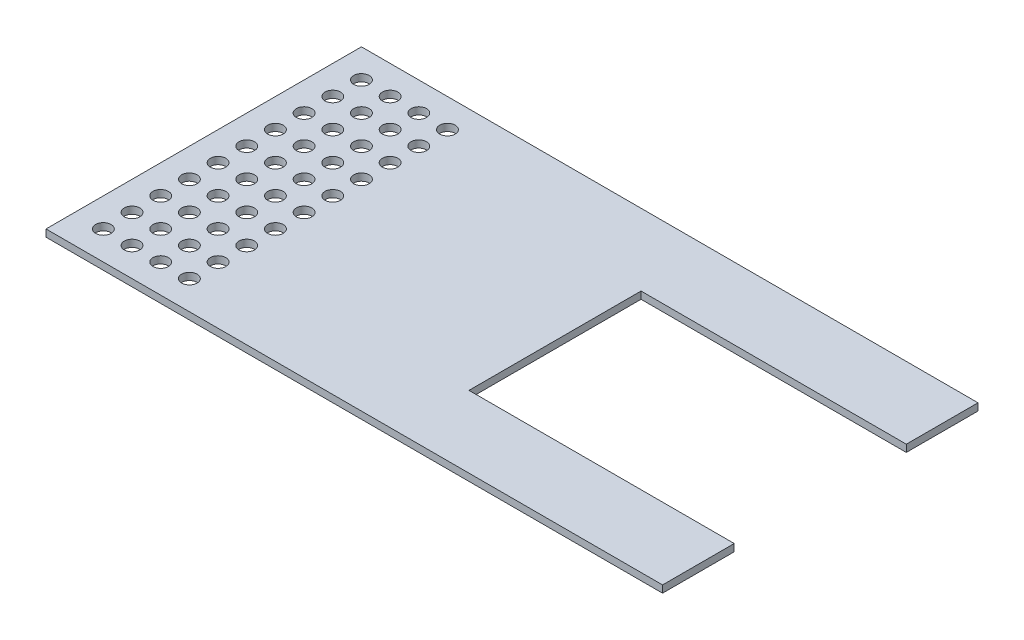
SolidWorks part; units mm, degrees
ref_plane "Front Plane" through (0, 0, 0) normal (0, 0, 1) x (1, 0, 0)
ref_plane "Top Plane" through (0, 0, 0) normal (0, 1, 0) x (1, 0, 0)
ref_plane "Right Plane" through (0, 0, 0) normal (1, 0, 0) x (0, 0, -1)
sketch "Sketch1" plane through (0, 0, 0) normal (0, 1, 0) x (1, 0, 0)
  line L1 (-101.6, -66.675) -> (101.6, -66.675)
  line L2 (-101.6, -66.675) -> (-101.6, 66.675)
  line L3 (-101.6, 66.675) -> (101.6, 66.675)
  line L4 (101.6, -66.675) -> (101.6, 66.675)
  line L5 (-101.6, -66.675) -> (101.6, 66.675) construction
  line L6 (-101.6, 66.675) -> (101.6, -66.675) construction
  point P0 (0, 0)
  dimension "D1" = 203.2
  dimension "D2" = 133.35
extrude "Boss-Extrude1" add sketch "Sketch1" along normal blind 3.175
sketch "Sketch3" plane through (0, 3.175, 0) normal (0, 1, 0) x (1, 0, 0)
  line L0 (101.6, 66.675) -> (-101.6, 66.675) construction
  line L1 (-79.121, 66.675) -> (-43.434, 66.675)
  line L2 (-79.121, 66.675) -> (-79.121, 69.85)
  line L3 (-79.121, 69.85) -> (-43.434, 69.85)
  line L4 (-43.434, 66.675) -> (-43.434, 69.85)
  line L5 (-101.6, 66.675) -> (-101.6, -66.675) construction
  line L6 (-17.526, 66.675) -> (18.161, 66.675)
  line L7 (18.161, 66.675) -> (18.161, 69.85)
  line L8 (-17.526, 69.85) -> (18.161, 69.85)
  line L9 (-17.526, 66.675) -> (-17.526, 69.85)
  line L10 (44.069, 66.675) -> (79.756, 66.675)
  line L11 (79.756, 66.675) -> (79.756, 69.85)
  line L12 (44.069, 69.85) -> (79.756, 69.85)
  line L13 (44.069, 66.675) -> (44.069, 69.85)
  line L14 (0, 0) -> (101.6, 0) construction
  line L15 (101.6, -66.675) -> (101.6, 66.675) construction
  line L16 (44.069, -66.675) -> (44.069, -69.85)
  line L17 (44.069, -69.85) -> (79.756, -69.85)
  line L18 (79.756, -66.675) -> (79.756, -69.85)
  line L19 (44.069, -66.675) -> (79.756, -66.675)
  line L20 (-17.526, -66.675) -> (-17.526, -69.85)
  line L21 (-17.526, -69.85) -> (18.161, -69.85)
  line L22 (18.161, -66.675) -> (18.161, -69.85)
  line L23 (-17.526, -66.675) -> (18.161, -66.675)
  line L24 (-43.434, -66.675) -> (-43.434, -69.85)
  line L25 (-79.121, -69.85) -> (-43.434, -69.85)
  line L26 (-79.121, -66.675) -> (-79.121, -69.85)
  line L27 (-79.121, -66.675) -> (-43.434, -66.675)
  point P6 (-61.2775, 66.675)
  dimension "D1" = 3.175
  dimension "D2" = 40.3225
  dimension "D3" = 22.479
  dimension "D4" = 35.687
  dimension "D5" = 3
extrude "Boss-Extrude2" add sketch "Sketch3" against normal blind 3.175
sketch "Sketch4" plane through (0, 3.175, 0) normal (0, 1, 0) x (1, 0, 0)
  line L0 (-101.6, 66.675) -> (-101.6, -66.675) construction
  line L1 (-101.6, 47.371) -> (-104.775, 47.371)
  line L2 (-101.6, 47.371) -> (-101.6, 28.829)
  line L3 (-101.6, 28.829) -> (-104.775, 28.829)
  line L4 (-104.775, 47.371) -> (-104.775, 28.829)
  line L5 (-104.775, 9.271) -> (-104.775, -9.271)
  line L6 (-79.121, 66.675) -> (-101.6, 66.675) construction
  line L7 (-101.6, -9.271) -> (-104.775, -9.271)
  line L8 (-101.6, 9.271) -> (-101.6, -9.271)
  line L9 (-101.6, 9.271) -> (-104.775, 9.271)
  line L10 (-104.775, -28.829) -> (-104.775, -47.371)
  line L11 (-101.6, -47.371) -> (-104.775, -47.371)
  line L12 (-101.6, -28.829) -> (-101.6, -47.371)
  line L13 (-101.6, -28.829) -> (-104.775, -28.829)
  line L14 (0, 0) -> (0, 30.8846) construction
  line L15 (101.6, -28.829) -> (104.775, -28.829)
  line L16 (101.6, -28.829) -> (101.6, -47.371)
  line L17 (101.6, -47.371) -> (104.775, -47.371)
  line L18 (104.775, -28.829) -> (104.775, -47.371)
  line L19 (101.6, 9.271) -> (104.775, 9.271)
  line L20 (101.6, 9.271) -> (101.6, -9.271)
  line L21 (101.6, -9.271) -> (104.775, -9.271)
  line L22 (104.775, 9.271) -> (104.775, -9.271)
  line L23 (104.775, 47.371) -> (104.775, 28.829)
  line L24 (101.6, 28.829) -> (104.775, 28.829)
  line L25 (101.6, 47.371) -> (101.6, 28.829)
  line L26 (101.6, 47.371) -> (104.775, 47.371)
  point P9 (-101.6, 38.1)
  point P10 (-103.1875, 47.371)
  dimension "D1" = 3.175
  dimension "D2" = 28.575
  dimension "D3" = 18.542
  dimension "D4" = 19.304
  dimension "D6" = 38.1
  dimension "D5" = 3
extrude "Boss-Extrude3" add sketch "Sketch4" against normal blind 3.175
sketch "Sketch5" plane through (0, 3.175, 0) normal (0, 1, 0) x (1, 0, 0)
  line L1 (-104.775, 69.85) -> (-168.275, 69.85)
  line L3 (-104.775, -69.85) -> (-168.275, -69.85)
  line L4 (-168.275, 69.85) -> (-168.275, -69.85)
  line L5 (-79.121, -69.85) -> (-43.434, -69.85) construction
  line L6 (-43.434, 69.85) -> (-79.121, 69.85) construction
  line L7 (104.775, 28.829) -> (104.775, 47.371) construction
  line L8 (-104.775, -69.85) -> (104.775, -69.85)
  line L10 (-104.775, 69.85) -> (104.775, 69.85)
  line L11 (104.775, -69.85) -> (104.775, 69.85)
  circle A0 centre (-117.475, 57.15) radius 3.429
  circle A1 centre (-130.175, 57.15) radius 3.429
  circle A2 centre (-142.875, 57.15) radius 3.429
  circle A3 centre (-155.575, 57.15) radius 3.429
  circle A4 centre (-130.175, 44.45) radius 3.429
  circle A5 centre (-142.875, 44.45) radius 3.429
  circle A6 centre (-155.575, 44.45) radius 3.429
  circle A7 centre (-130.175, 31.75) radius 3.429
  circle A8 centre (-142.875, 31.75) radius 3.429
  circle A9 centre (-155.575, 31.75) radius 3.429
  circle A10 centre (-130.175, 19.05) radius 3.429
  circle A11 centre (-142.875, 19.05) radius 3.429
  circle A12 centre (-155.575, 19.05) radius 3.429
  circle A13 centre (-130.175, 6.35) radius 3.429
  circle A14 centre (-142.875, 6.35) radius 3.429
  circle A15 centre (-155.575, 6.35) radius 3.429
  circle A16 centre (-130.175, -6.35) radius 3.429
  circle A17 centre (-142.875, -6.35) radius 3.429
  circle A18 centre (-155.575, -6.35) radius 3.429
  circle A19 centre (-130.175, -19.05) radius 3.429
  circle A20 centre (-142.875, -19.05) radius 3.429
  circle A21 centre (-155.575, -19.05) radius 3.429
  circle A22 centre (-130.175, -31.75) radius 3.429
  circle A23 centre (-142.875, -31.75) radius 3.429
  circle A24 centre (-155.575, -31.75) radius 3.429
  circle A25 centre (-130.175, -44.45) radius 3.429
  circle A26 centre (-142.875, -44.45) radius 3.429
  circle A27 centre (-155.575, -44.45) radius 3.429
  circle A28 centre (-130.175, -57.15) radius 3.429
  circle A29 centre (-142.875, -57.15) radius 3.429
  circle A30 centre (-155.575, -57.15) radius 3.429
  circle A31 centre (-117.475, 44.45) radius 3.429
  circle A32 centre (-117.475, 31.75) radius 3.429
  circle A33 centre (-117.475, 19.05) radius 3.429
  circle A34 centre (-117.475, 6.35) radius 3.429
  circle A35 centre (-117.475, -6.35) radius 3.429
  circle A36 centre (-117.475, -19.05) radius 3.429
  circle A37 centre (-117.475, -31.75) radius 3.429
  circle A38 centre (-117.475, -44.45) radius 3.429
  circle A39 centre (-117.475, -57.15) radius 3.429
  dimension "D1" = 6.858
  dimension "D6" = 63.5
  dimension "D2" = 12.7
  dimension "D4" = 4
  dimension "D5" = 10
extrude "Boss-Extrude4" add sketch "Sketch5" against normal blind 3.175
sketch "Sketch8" plane through (0, 0, 0) normal (0, 1, 0) x (1, 0, 0)
  line L1 (114.3, 38.1) -> (-12.7, 38.1)
  line L2 (114.3, 38.1) -> (114.3, -38.1)
  line L3 (114.3, -38.1) -> (-12.7, -38.1)
  line L4 (-12.7, 38.1) -> (-12.7, -38.1)
  line L5 (114.3, 38.1) -> (-12.7, -38.1) construction
  line L6 (114.3, -38.1) -> (-12.7, 38.1) construction
  line L7 (104.775, -69.85) -> (104.775, 69.85) construction
  point P0 (50.8, 0)
  dimension "D1" = 76.2
  dimension "D2" = 127
  dimension "D3" = 53.975
extrude "Cut-Extrude4" cut sketch "Sketch8" along normal through all
